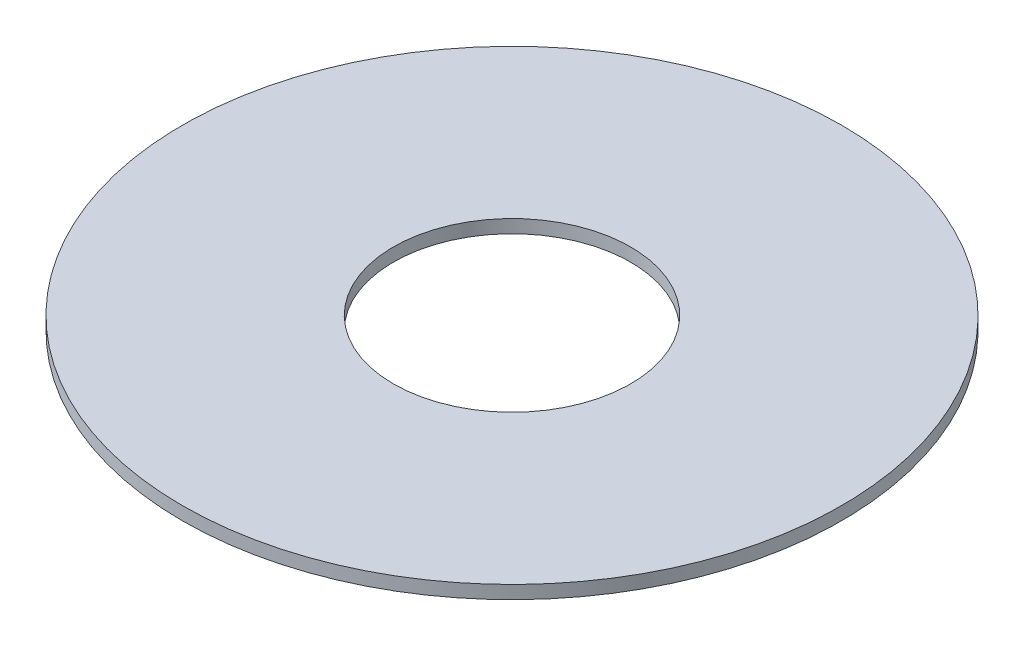
SolidWorks part; units mm, degrees
material "Plain Carbon Steel"
ref_plane "Front Plane" through (0, 0, 0) normal (0, 0, 1) x (1, 0, 0)
ref_plane "Top Plane" through (0, 0, 0) normal (0, 1, 0) x (1, 0, 0)
ref_plane "Right Plane" through (0, 0, 0) normal (1, 0, 0) x (0, 0, -1)
sketch "Sketch1" plane through (0, 0, 0) normal (0, 1, 0) x (1, 0, 0)
  circle A0 centre (0, 0) radius 25
  circle A1 centre (0, 0) radius 9
  dimension "D1" = 50
  dimension "D2" = 18
extrude "Boss-Extrude1" add sketch "Sketch1" along normal blind 1
